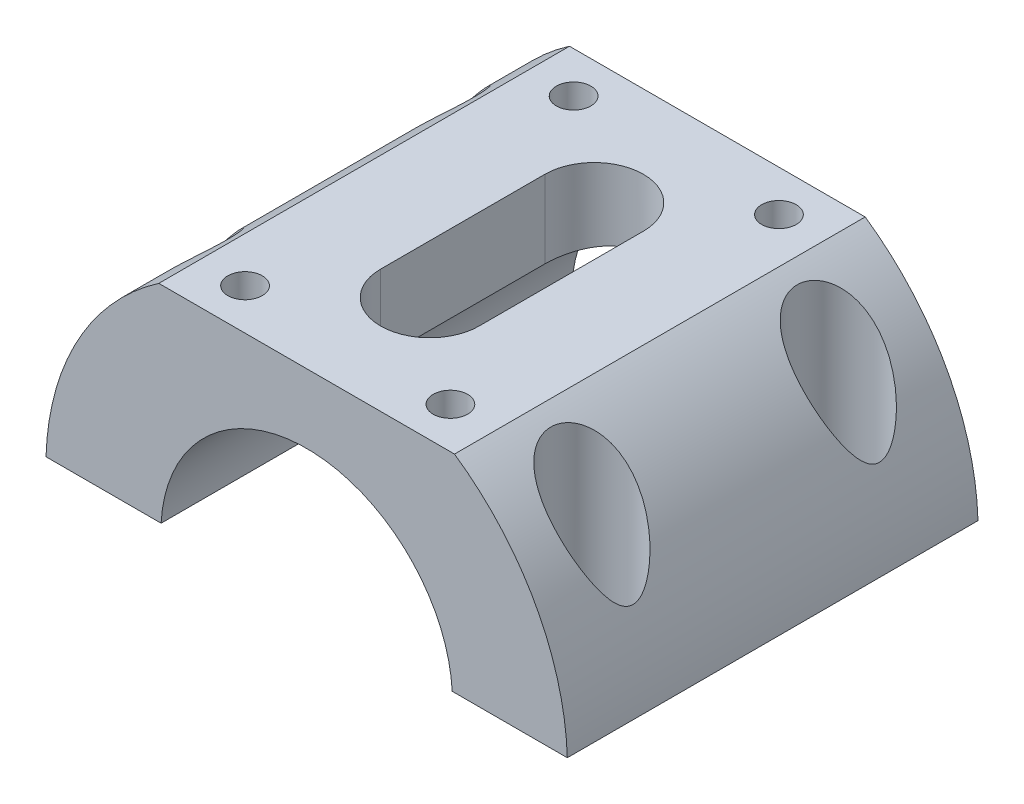
SolidWorks part; units mm, degrees
ref_plane "Front" through (0, 0, 0) normal (0, 0, 1) x (1, 0, 0)
ref_plane "Top" through (0, 0, 0) normal (0, 1, 0) x (1, 0, 0)
ref_plane "Right" through (0, 0, 0) normal (1, 0, 0) x (0, 0, -1)
sketch "Sketch1" plane through (0, 0, 0) normal (0, 0, 1) x (1, 0, 0)
  line L0 (-31.75, 0) -> (31.75, 0) construction
  line L1 (-31.7342, 1) -> (-17.7218, 1)
  line L2 (-31.75, 1) -> (31.75, 1) construction
  line L3 (17.7218, 1) -> (31.7342, 1)
  arc A0 (31.7342, 1) -> (-31.7342, 1) centre (0, 0) ccw
  arc A1 (17.7218, 1) -> (-17.7218, 1) centre (0, 0) ccw
  dimension "D1" = 35.5
  dimension "D2" = 63.5
  dimension "D3" = 1
extrude "Boss-Extrude1" add sketch "Sketch1" along normal blind 50
sketch "Sketch2" plane through (0, 1, 0) normal (0, -1, 0) x (-1, 0, 0)
  line L0 (24.728, -50) -> (24.728, 0) construction
  line L1 (31.7342, -50) -> (17.7218, -50) construction
  line L2 (31.7342, 0) -> (17.7218, 0) construction
  line L3 (-24.728, -50) -> (-24.728, 0) construction
  line L4 (-17.7218, -50) -> (-31.7342, -50) construction
  line L5 (-17.7218, 0) -> (-31.7342, 0) construction
  line L6 (0, -50) -> (0, 0) construction
  line L7 (-17.7218, -50) -> (17.7218, -50) construction
  circle A0 centre (24.728, -40) radius 1
  circle A1 centre (24.728, -10) radius 1
  circle A2 centre (-24.728, -10) radius 1
  circle A3 centre (-24.728, -40) radius 1
  dimension "D1" = 10
  dimension "D2" = 10
  dimension "D3" = 2
hole_wizard "Ø5.0mm Clearance Dowel Hole1" positions "3DSketch1" profile "Sketch3" hole size "Ø5.0" standard "ANSI Metric" end condition up to next
sketch3d "3DSketch1"
  point P0 (-24.728, 1, 40)
  point P3 (-24.728, 1, 10)
  point P6 (24.728, 1, 40)
  point P9 (24.728, 1, 10)
sketch "Sketch3" plane through (-24.728, 1, 40) normal (1, 0, 0) x (0, 0, -1)
  line L0 (0, 0) -> (0, 18.9145)
  line L1 (0, 18.9145) -> (2.5, 18.9145)
  line L2 (2.5, 18.9145) -> (2.5, 0)
  line L5 (2.5, 0) -> (0, 0)
  line L11 (0, -6.35) -> (0, 107.95) construction
  dimension "Thru Hole Dia." = 5
  dimension "Thru Hole Depth" = 18.9145
ref_plane "Plane1" through (0, 4, 0) normal (0, -1, 0) x (-1, 0, 0)
sketch "Sketch4" plane through (0, 4, 0) normal (0, -1, 0) x (-1, 0, 0)
  circle A0 centre (24.728, -40) radius 5
  circle A1 centre (24.728, -10) radius 5
  circle A2 centre (-24.728, -10) radius 5
  circle A3 centre (-24.728, -40) radius 5
  dimension "D1" = 10
extrude "Cut-Extrude1" cut sketch "Sketch4" against normal up to next
sketch "Sketch5" plane through (0, 1, 0) normal (0, -1, 0) x (-1, 0, 0)
  line L0 (0, -50) -> (0, 0) construction
  line L1 (-17.7218, -50) -> (17.7218, -50) construction
  line L2 (0, -35) -> (0, -15) construction
  line L3 (-6, -35) -> (-6, -15)
  line L4 (6, -35) -> (6, -15)
  arc A1 (-6, -35) -> (6, -35) centre (0, -35) ccw
  arc A2 (6, -15) -> (-6, -15) centre (0, -15) ccw
  point P9 (0, -25)
  dimension "D1" = 12
  dimension "D2" = 20
extrude "Cut-Extrude2" cut sketch "Sketch5" against normal up to next
sketch "Sketch6" plane through (0, 0, 50) normal (0, 0, 1) x (1, 0, 0)
  line L0 (18, 26.1546) -> (-18, 26.1546)
  arc A0 (31.7342, 1) -> (-31.7342, 1) centre (0, 0) ccw construction
  arc A1 (18, 26.1546) -> (-18, 26.1546) centre (0, 0) ccw
  dimension "D1" = 36
extrude "Cut-Extrude3" cut sketch "Sketch6" against normal through all
sketch "Sketch7" plane through (0, 26.1546, 0) normal (0, 1, 0) x (1, 0, 0)
  line L0 (0, -50) -> (0, 0) construction
  line L1 (-12.5, -45) -> (12.5, -45) construction
  line L2 (-12.5, -45) -> (-12.5, -5) construction
  line L3 (-12.5, -5) -> (12.5, -5) construction
  line L4 (12.5, -45) -> (12.5, -5) construction
  line L5 (-12.5, -45) -> (12.5, -5) construction
  line L6 (-12.5, -5) -> (12.5, -45) construction
  circle A0 centre (12.5, -5) radius 0.75
  circle A1 centre (-12.5, -5) radius 0.75
  circle A2 centre (12.5, -45) radius 0.75
  circle A3 centre (-12.5, -45) radius 0.75
  point P0 (0, -25)
  dimension "D3" = 1.5
  dimension "D1" = 40
  dimension "D2" = 25
hole_wizard "Tap Drill for M5x0.8 Tap1" positions "3DSketch2" profile "Sketch8" hole size "M5x0.8" standard "ANSI Metric"
sketch3d "3DSketch2"
  point P0 (-12.5, 26.1546, 5)
  point P3 (-12.5, 26.1546, 45)
  point P6 (12.5, 26.1546, 45)
  point P9 (12.5, 26.1546, 5)
sketch "Sketch8" plane through (-12.5, 26.1546, 5) normal (1, 0, 0) x (0, 0, 1)
  line L0 (0, 0) -> (0, 9.2618)
  line L1 (0, 9.2618) -> (2.1, 8)
  line L2 (2.1, 8) -> (2.1, 0)
  line L5 (2.1, 0) -> (0, 0)
  line L10 (0, 9.2618) -> (-2.1, 8) construction
  line L11 (0, -6.35) -> (0, 107.95) construction
  dimension "Hole Dia." = 4.2
  dimension "Hole Depth" = 8
  dimension "Drill Angle" = 118
